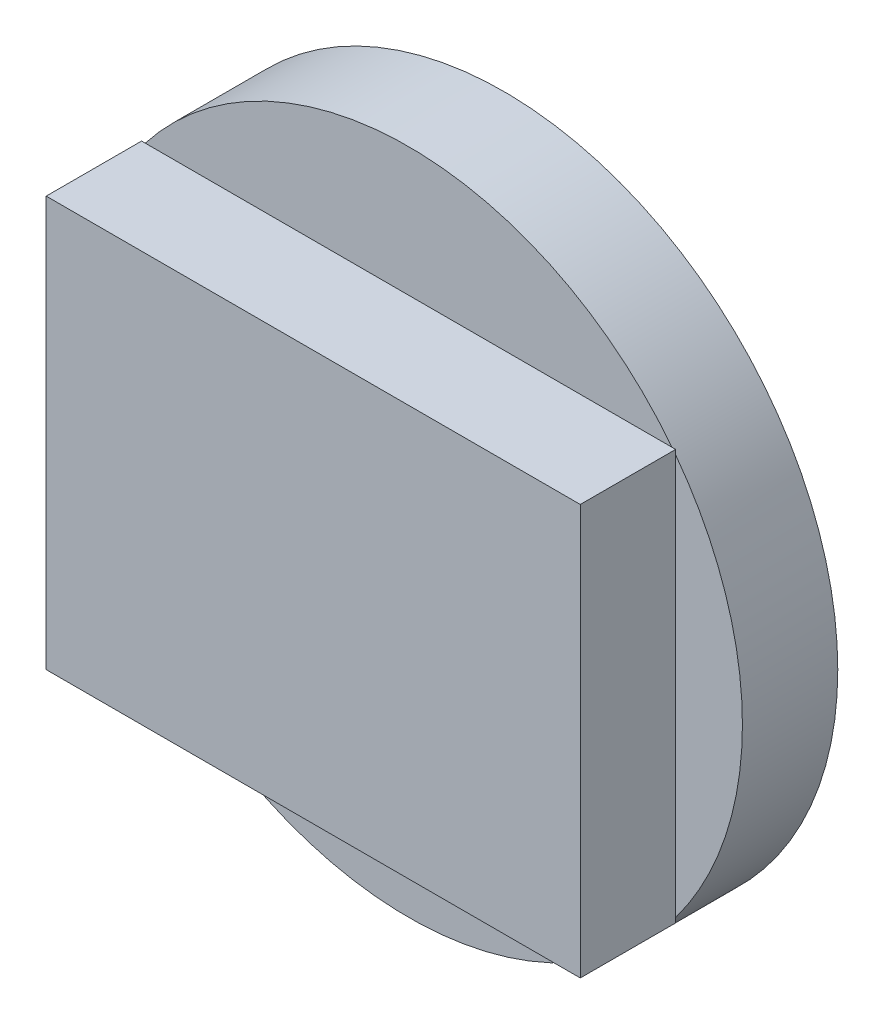
SolidWorks part; units mm, degrees
ref_plane "Plan de face" through (0, 0, 0) normal (0, 0, 1) x (1, 0, 0)
ref_plane "Plan de dessus" through (0, 0, 0) normal (0, 1, 0) x (1, 0, 0)
ref_plane "Plan de droite" through (0, 0, 0) normal (1, 0, 0) x (0, 0, -1)
sketch "Esquisse1" plane through (0, 0, 0) normal (0, 0, 1) x (1, 0, 0)
  line L1 (-6.2653, 4.8333) -> (-0.6653, 4.8333)
  line L2 (-6.2653, 4.8333) -> (-6.2653, 0.5333)
  line L3 (-6.2653, 0.5333) -> (-0.6653, 0.5333)
  line L4 (-0.6653, 4.8333) -> (-0.6653, 0.5333)
  dimension "D1" = 5.6
  dimension "D2" = 4.3
extrude "Boss.-Extru.1" add sketch "Esquisse1" along normal blind 1
sketch "Esquisse2" plane through (0, 0, 0) normal (0, 0, 1) x (1, 0, 0)
  line L0 (-6.2653, 4.8333) -> (-6.2653, 0.5333) construction
  line L1 (-6.2653, 0.5333) -> (-0.6653, 0.5333) construction
  circle A0 centre (-3.4653, 2.6833) radius 3.5
  dimension "D3" = 7
  dimension "D1" = 2.8
  dimension "D2" = 2.15
extrude "Boss.-Extru.2" add sketch "Esquisse2" against normal blind 1 contours A0
